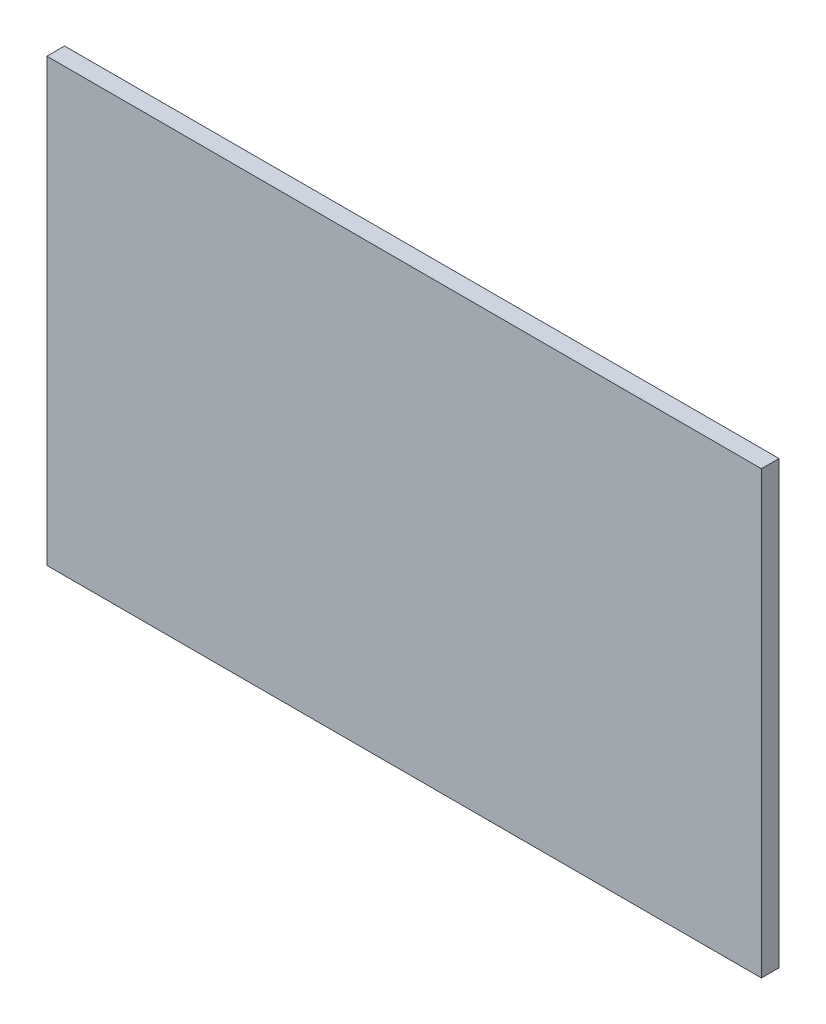
SolidWorks part; units mm, degrees
ref_plane "Спереди" through (0, 0, 0) normal (0, 0, 1) x (1, 0, 0)
ref_plane "Сверху" through (0, 0, 0) normal (0, 1, 0) x (1, 0, 0)
ref_plane "Справа" through (0, 0, 0) normal (1, 0, 0) x (0, 0, -1)
sketch "Эскиз1" plane through (0, 0, 0) normal (0, 0, 1) x (1, 0, 0)
  line L1 (-56.9486, 38.0705) -> (591.0514, 38.0705)
  line L2 (-56.9486, 38.0705) -> (-56.9486, -361.9295)
  line L3 (-56.9486, -361.9295) -> (591.0514, -361.9295)
  line L4 (591.0514, 38.0705) -> (591.0514, -361.9295)
  dimension "D1" = 648
  dimension "D2" = 400
extrude "Бобышка-Вытянуть1" add sketch "Эскиз1" along normal blind 16
